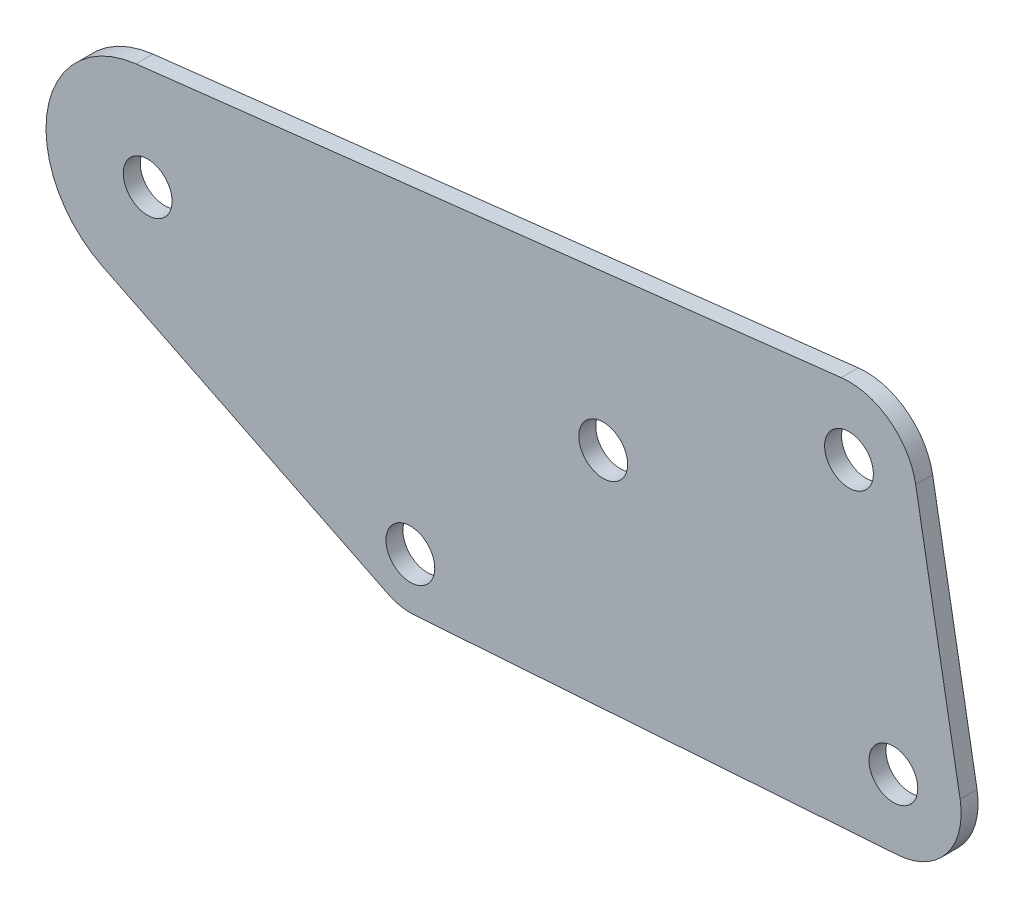
SolidWorks part; units mm, degrees
material "Delrin 2700 NC010, Low Viscosity Acetal Copolymer (SS)"
ref_plane "Front Plane" through (0, 0, 0) normal (0, 0, 1) x (1, 0, 0)
ref_plane "Top Plane" through (0, 0, 0) normal (0, 1, 0) x (1, 0, 0)
ref_plane "Right Plane" through (0, 0, 0) normal (1, 0, 0) x (0, 0, -1)
sketch "Sketch1" plane through (0, 0, 0) normal (0, 0, 1) x (1, 0, 0)
  line L0 (65.6922, 10.7345) -> (42.672, 0) construction
  line L1 (64.9683, 17.0431) -> (-1.0859, 9.4629)
  line L2 (-4.2174, -8.5404) -> (22.4975, -21.7327)
  line L5 (0, 0) -> (42.672, 0) construction
  line L6 (24.6063, -17.4625) -> (24.6062, 0) construction
  line L7 (0, 0) -> (47.7528, 0) construction
  line L8 (24.9392, -22.2133) -> (70.294, -19.0345)
  line L9 (76.1024, -11.5907) -> (71.9446, 11.8438)
  circle A0 centre (0, 0) radius 2.286
  circle A1 centre (42.672, 0) radius 2.286
  circle A2 centre (65.6922, 10.7345) radius 2.286
  circle A3 centre (24.6063, -17.4625) radius 2.286
  arc A4 (-1.0859, 9.4629) -> (-4.2174, -8.5404) centre (0, 0) ccw
  arc A5 (22.4975, -21.7327) -> (24.9392, -22.2133) centre (24.6063, -17.4625) ccw
  arc A7 (71.9446, 11.8438) -> (64.9683, 17.0431) centre (65.6922, 10.7345) ccw
  circle A8 centre (69.85, -12.7) radius 2.286
  arc A9 (76.1024, -11.5907) -> (70.294, -19.0345) centre (69.85, -12.7) cw
  dimension "D5" = 4.572
  dimension "D6" = 4.572
  dimension "D7" = 155
  dimension "D8" = 9.525
  dimension "D10" = 6.35
  dimension "D11" = 4.7625
  dimension "D15" = 6.35
  dimension "D1" = 42.672
  dimension "D2" = 25.4
  dimension "D3" = 17.4625
  dimension "D4" = 0
  dimension "D12" = 24.6062
  dimension "D13" = 12.7
  dimension "D14" = 69.85
extrude "Boss-Extrude1" add sketch "Sketch1" along normal blind 1.5875
